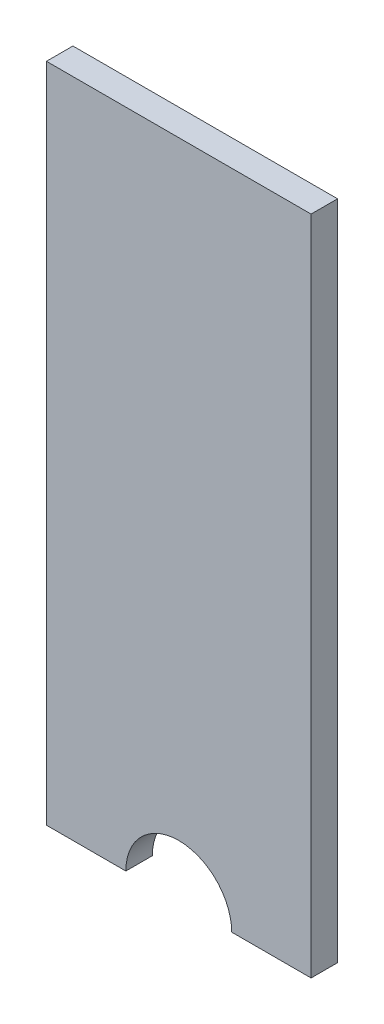
SolidWorks part; units mm, degrees
ref_plane "Front Plane" through (0, 0, 0) normal (0, 0, 1) x (1, 0, 0)
ref_plane "Top Plane" through (0, 0, 0) normal (0, 1, 0) x (1, 0, 0)
ref_plane "Right Plane" through (0, 0, 0) normal (1, 0, 0) x (0, 0, -1)
sketch "Sketch1" plane through (0, 0, 0) normal (0, 0, 1) x (1, 0, 0)
  line L0 (-161.4146, 340.3953) -> (38.5854, 340.3953)
  line L1 (38.5854, 340.3953) -> (38.5854, -159.6047)
  line L2 (38.5854, -159.6047) -> (-161.4146, -159.6047)
  line L3 (-161.4146, -159.6047) -> (-161.4146, 340.3953)
  dimension "D1" = 500
  dimension "D2" = 200
extrude "Boss-Extrude1" add sketch "Sketch1" along normal blind 20
sketch "Sketch2" plane through (0, 0, 20) normal (0, 0, 1) x (1, 0, 0)
  line L0 (-161.4146, -159.6047) -> (38.5854, -159.6047) construction
  circle A0 centre (-61.4146, -159.6047) radius 40
  dimension "D1" = 80
extrude "Cut-Extrude1" cut sketch "Sketch2" against normal blind 68
